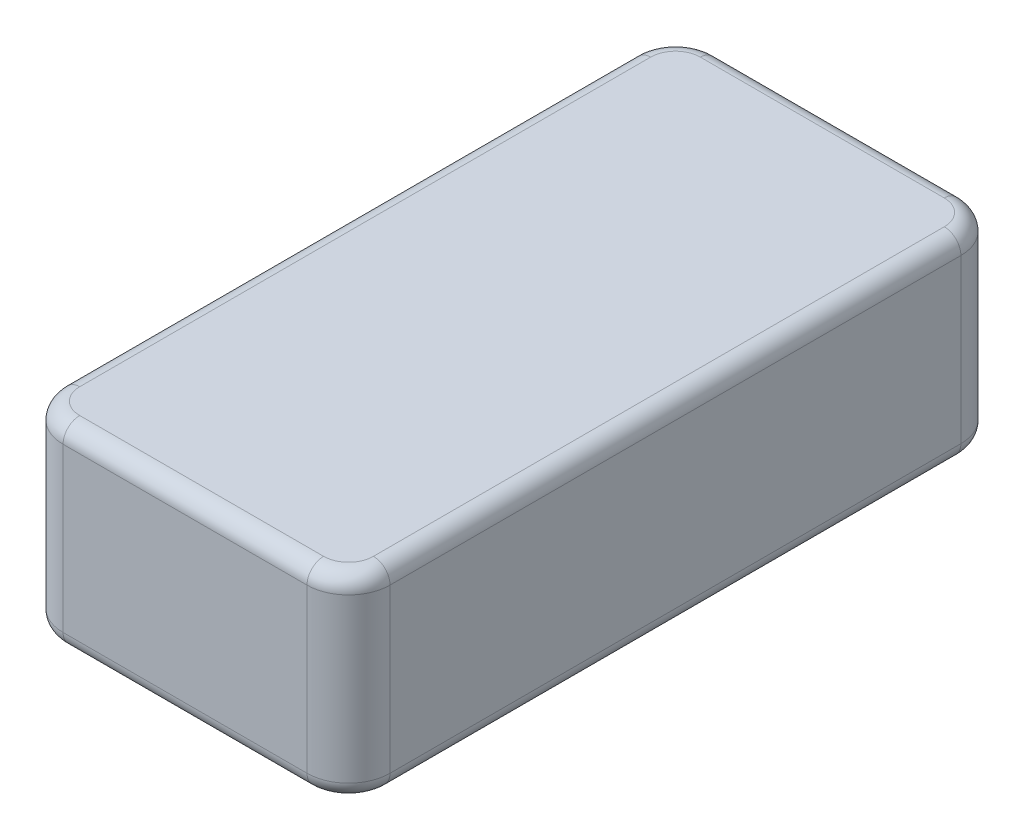
SolidWorks part; units mm, degrees
ref_plane "Front Plane" through (0, 0, 0) normal (0, 0, 1) x (1, 0, 0)
ref_plane "Top Plane" through (0, 0, 0) normal (0, 1, 0) x (1, 0, 0)
ref_plane "Right Plane" through (0, 0, 0) normal (1, 0, 0) x (0, 0, -1)
sketch "Sketch1" plane through (0, 0, 0) normal (0, 1, 0) x (1, 0, 0)
  line L1 (0, 0) -> (5, 0)
  line L2 (0, 0) -> (0, 10)
  line L3 (0, 10) -> (5, 10)
  line L4 (5, 0) -> (5, 10)
  dimension "D1" = 10
  dimension "D2" = 5
extrude "Boss-Extrude1" add sketch "Sketch1" along normal blind 3
fillet "Fillet1" radius 0.635 4 edges at (0, 1.5, -10) (5, 1.5, -10) (5, 1.5, 0) (0, 1.5, 0)
fillet "Fillet2" radius 0.254 16 edges at (0.186, 0, -0.186) (2.5, 0, 0) (4.814, 0, -0.186) (5, 0, -5) (4.814, 0, -9.814) (2.5, 0, -10) (0.186, 0, -9.814) (0, 0, -5) (4.814, 3, -9.814) (5, 3, -5) (4.814, 3, -0.186) (2.5, 3, 0) (0.186, 3, -0.186) (0, 3, -5) (0.186, 3, -9.814) (2.5, 3, -10)
